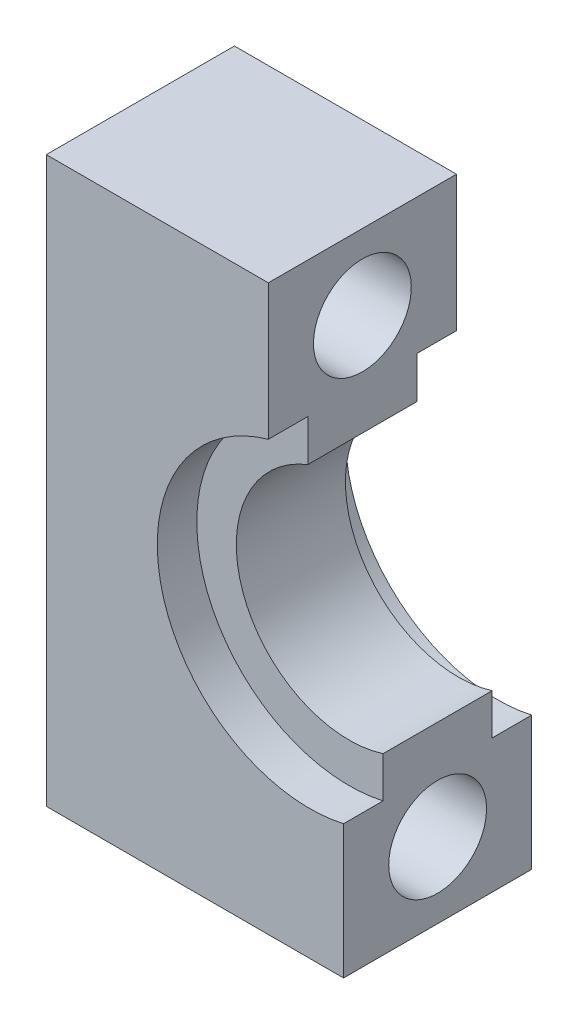
SolidWorks part; units mm, degrees
ref_plane "Front Plane" through (0, 0, 0) normal (0, 0, 1) x (1, 0, 0)
ref_plane "Top Plane" through (0, 0, 0) normal (0, 1, 0) x (1, 0, 0)
ref_plane "Right Plane" through (0, 0, 0) normal (1, 0, 0) x (0, 0, -1)
sketch "Sketch3" plane through (0, 0, 0) normal (0, 0, 1) x (1, 0, 0)
  line L0 (0, -15) -> (0, 15)
  line L1 (0, 15) -> (11.8, 15)
  line L2 (0, -15) -> (15.8, -15)
  line L3 (5.5, 0) -> (-5.5, 0) construction
  line L4 (0, -5.5) -> (0, 5.5) construction
  line L5 (11.8, 15) -> (11.8, 7.7955)
  line L6 (15.8, -15) -> (15.8, -7.8975)
  arc A0 (11.8, 7.7955) -> (15.8, -7.8975) centre (14, 0) ccw
  dimension "D1" = 16.2
  dimension "D2" = 30
  dimension "D3" = 15
  dimension "D4" = 14
  dimension "D5" = 11.8
  dimension "D6" = 15.8
extrude "Boss-Extrude2" add sketch "Sketch3" along normal mid plane 10
sketch "Sketch4" plane through (0, 0, 0) normal (0, 0, 1) x (1, 0, 0)
  line L0 (11.8, 8.2104) -> (11.8, 5.5821)
  line L1 (15.8, -5.7236) -> (15.8, -8.3072)
  arc A0 (11.8, 5.5821) -> (15.8, -5.7236) centre (14, 0) ccw
  arc A1 (11.8, 8.2104) -> (15.8, -8.3072) centre (14, 0) ccw
  dimension "D1" = 12
  dimension "D2" = 17
  dimension "D3" = 2.2
  dimension "D4" = 1.8
extrude "Boss-Extrude3" add sketch "Sketch4" along normal mid plane 5.8
sketch "Sketch5" plane through (0, 0, 0) normal (1, 0, 0) x (0, 0, -1)
  line L0 (0, 8.8) -> (0, -8.8) construction
  line L1 (5.5, 0) -> (-5.5, 0) construction
  circle A0 centre (0, 11) radius 2.6
  circle A1 centre (0, -11) radius 2.6
  dimension "D1" = 5.2
  dimension "D2" = 5.2
  dimension "D3" = 11
  dimension "D4" = 11
extrude "Cut-Extrude1" cut sketch "Sketch5" along normal up to next
